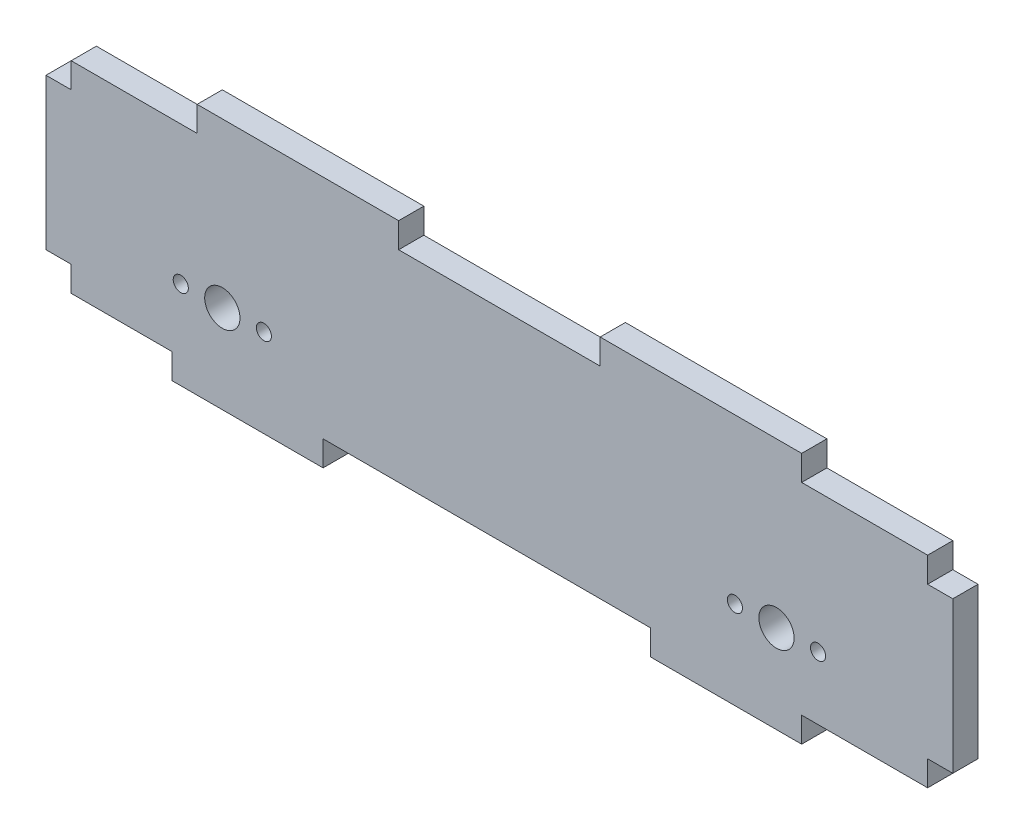
SolidWorks part; units mm, degrees
ref_plane "Front Plane" through (0, 0, 0) normal (0, 0, 1) x (1, 0, 0)
ref_plane "Top Plane" through (0, 0, 0) normal (0, 1, 0) x (1, 0, 0)
ref_plane "Right Plane" through (0, 0, 0) normal (1, 0, 0) x (0, 0, -1)
sketch "Sketch1" plane through (0, 0, 0) normal (0, 0, 1) x (1, 0, 0)
  line L0 (-30, -50.8914) -> (-30, -45.8914)
  line L1 (-30, -45.8914) -> (-5, -45.8914)
  line L2 (-10, -85.8914) -> (-30, -85.8914)
  line L3 (115, -85.8914) -> (110, -85.8914)
  line L4 (-5, -45.8914) -> (-5, -40.8914)
  line L5 (140, -45.8914) -> (115, -45.8914)
  line L6 (110, -73.3914) -> (101.75, -73.3914)
  line L7 (140, -45.8914) -> (140, -50.8914)
  line L8 (-30, -80.8914) -> (-35, -80.8914)
  line L9 (35, -45.8914) -> (35, -40.8914)
  line L10 (101.75, -73.3914) -> (118.25, -73.3914)
  line L11 (35, -40.8914) -> (-5, -40.8914)
  line L12 (0, -73.3914) -> (8.25, -73.3914)
  line L13 (20, -85.8914) -> (85, -85.8914)
  line L14 (20, -85.8914) -> (20, -90.8914)
  line L15 (-30, -80.8914) -> (-30, -85.8914)
  line L16 (20, -90.8914) -> (-10, -90.8914)
  line L17 (-30, -50.8914) -> (-35, -50.8914)
  line L18 (-35, -80.8914) -> (-35, -50.8914)
  line L19 (8.25, -73.3914) -> (-8.25, -73.3914)
  line L20 (140, -85.8914) -> (85, -85.8914)
  line L23 (140, -85.8914) -> (115, -85.8914)
  line L26 (140, -80.8914) -> (140, -85.8914)
  line L29 (75, -45.8914) -> (35, -45.8914)
  line L30 (115, -45.8914) -> (115, -40.8914)
  line L31 (110, -85.8914) -> (110, -73.3914)
  line L36 (-30, -85.8914) -> (-14, -85.8914)
  line L38 (0, -85.8914) -> (0, -73.3914)
  line L39 (0, -85.8914) -> (-30, -85.8914)
  line L41 (140, -80.8914) -> (145, -80.8914)
  line L42 (115, -40.8914) -> (75, -40.8914)
  line L48 (75, -45.8914) -> (75, -40.8914)
  line L49 (140, -50.8914) -> (145, -50.8914)
  line L52 (145, -80.8914) -> (145, -50.8914)
  line L53 (-10, -85.8914) -> (-10, -90.8914)
  line L57 (115, -85.8914) -> (115, -90.8914)
  line L58 (115, -90.8914) -> (85, -90.8914)
  line L59 (85, -85.8914) -> (85, -90.8914)
  circle A0 centre (118.25, -73.3914) radius 1.5
  circle A1 centre (110, -73.3914) radius 3.5
  circle A2 centre (101.75, -73.3914) radius 1.5
  circle A3 centre (8.25, -73.3914) radius 1.5
  circle A4 centre (-8.25, -73.3914) radius 1.5
  circle A5 centre (0, -73.3914) radius 3.5
  dimension "D24" = 3
  dimension "D27" = 5
  dimension "D34" = 40
  dimension "D43" = 30
  dimension "D54" = 7
  dimension "D11" = 7
  dimension "D13" = 3
  dimension "D14" = 3
  dimension "D19" = 3
  dimension "D7" = 16.5
  dimension "D8" = 5
  dimension "D9" = 5
  dimension "D10" = 40
  dimension "D12" = 8.25
  dimension "D15" = 30
  dimension "D16" = 8.25
  dimension "D17" = 5
  dimension "D18" = 16.5
  dimension "D20" = 30
  dimension "D21" = 5
  dimension "D22" = 30
  dimension "D23" = 25
  dimension "D25" = 30
  dimension "D26" = 20
  dimension "D28" = 5
  dimension "D29" = 5
  dimension "D30" = 25
  dimension "D33" = 5
  dimension "D37" = 12.5
  dimension "D46" = 12.5
  dimension "D57" = 40
  dimension "D58" = 5
  dimension "D59" = 25
  dimension "D60" = 30
  dimension "D61" = 5
  dimension "D62" = 180
extrude "Boss-Extrude1" add sketch "Sketch1" along normal blind 5
